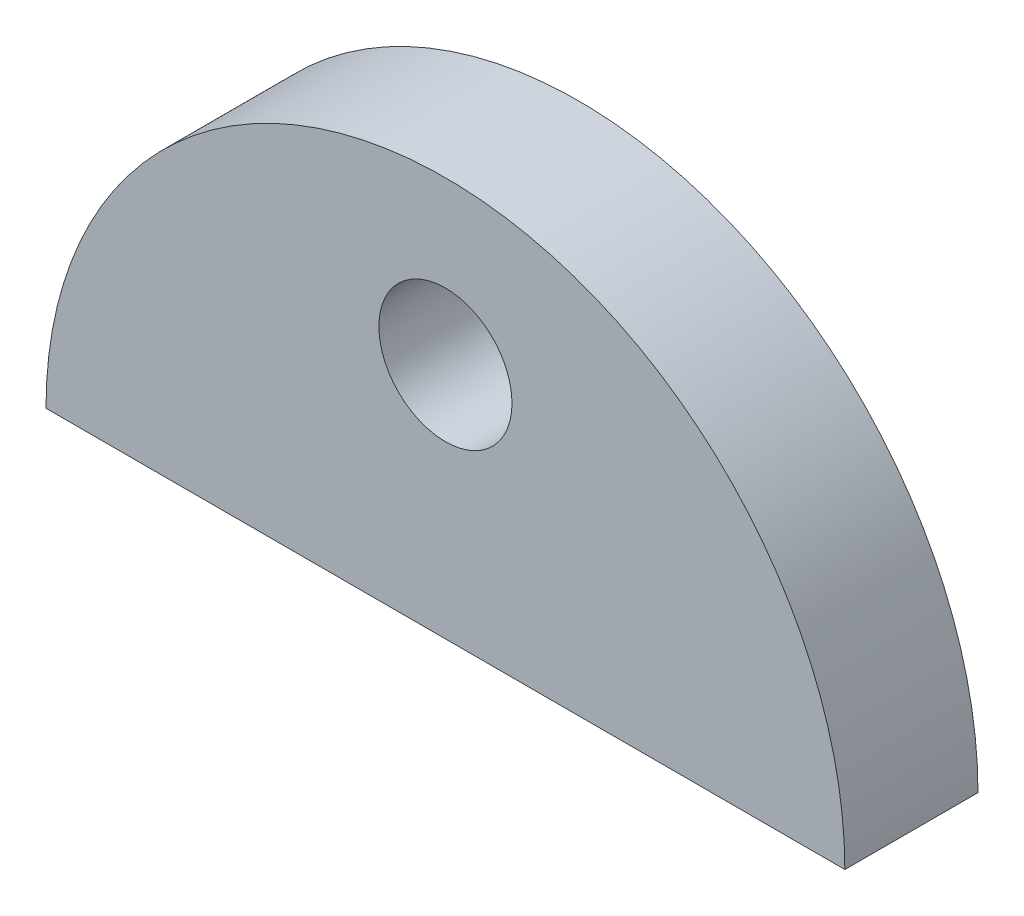
SolidWorks part; units mm, degrees
ref_plane "Front Plane" through (0, 0, 0) normal (0, 0, 1) x (1, 0, 0)
ref_plane "Top Plane" through (0, 0, 0) normal (0, 1, 0) x (1, 0, 0)
ref_plane "Right Plane" through (0, 0, 0) normal (1, 0, 0) x (0, 0, -1)
sketch "Sketch2" plane through (0, 0, 0) normal (0, 0, 1) x (1, 0, 0)
  line L0 (-38.1, 0) -> (0, 0)
  arc A0 (-38.1, 0) -> (0, 0) centre (-19.05, 0) cw
  circle A1 centre (-19.05, 11.3201) radius 3.175
  dimension "D1" = 38.1
  dimension "D2" = 6.35
extrude "Boss-Extrude1" add sketch "Sketch2" along normal blind 6.35
scale "Scale1" scale about centroid uniform scaling yes scale factor 1.5
